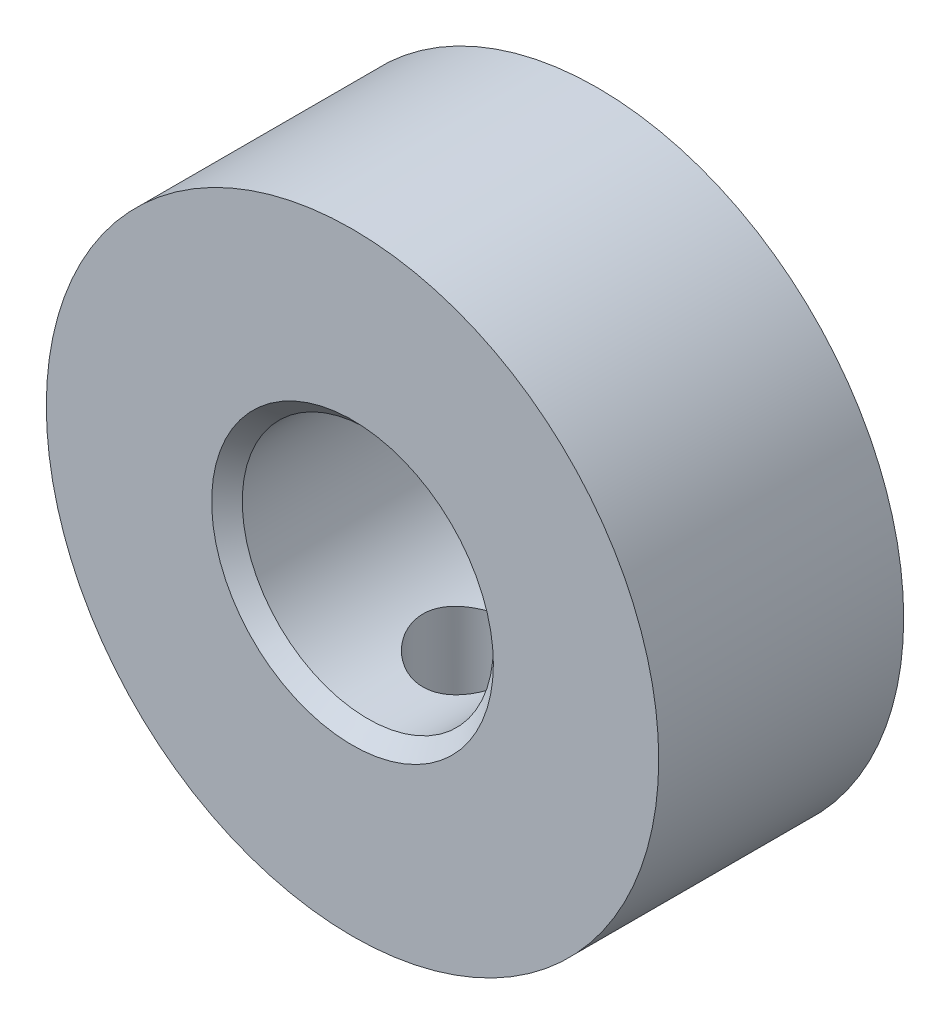
SolidWorks part; units mm, degrees
ref_plane "Plan de face" through (0, 0, 0) normal (0, 0, 1) x (1, 0, 0)
ref_plane "Plan de dessus" through (0, 0, 0) normal (0, 1, 0) x (1, 0, 0)
ref_plane "Plan de droite" through (0, 0, 0) normal (1, 0, 0) x (0, 0, -1)
sketch "Esquisse1" plane through (0, 0, 0) normal (0, 0, 1) x (1, 0, 0)
  circle A0 centre (0, 0) radius 4.1
  circle A1 centre (0, 0) radius 10
  dimension "D1" = 8.2
  dimension "D2" = 20
extrude "Boss.-Extru.1" add sketch "Esquisse1" along normal blind 8
sketch "Esquisse2" plane through (0, 0, 0) normal (0, 1, 0) x (1, 0, 0)
  line L0 (0, 0) -> (0, -8) construction
  line L1 (-10, -8) -> (10, -8) construction
  circle A0 centre (0, -4) radius 1.7
  dimension "D1" = 3.4
extrude "Enlèv. mat.-Extru.1" cut sketch "Esquisse2" against normal blind 15
chamfer "Chanfrein1" distance 0.5 angle 45 2 edges at (4.1, 0, 0) (4.1, 0, 8)
